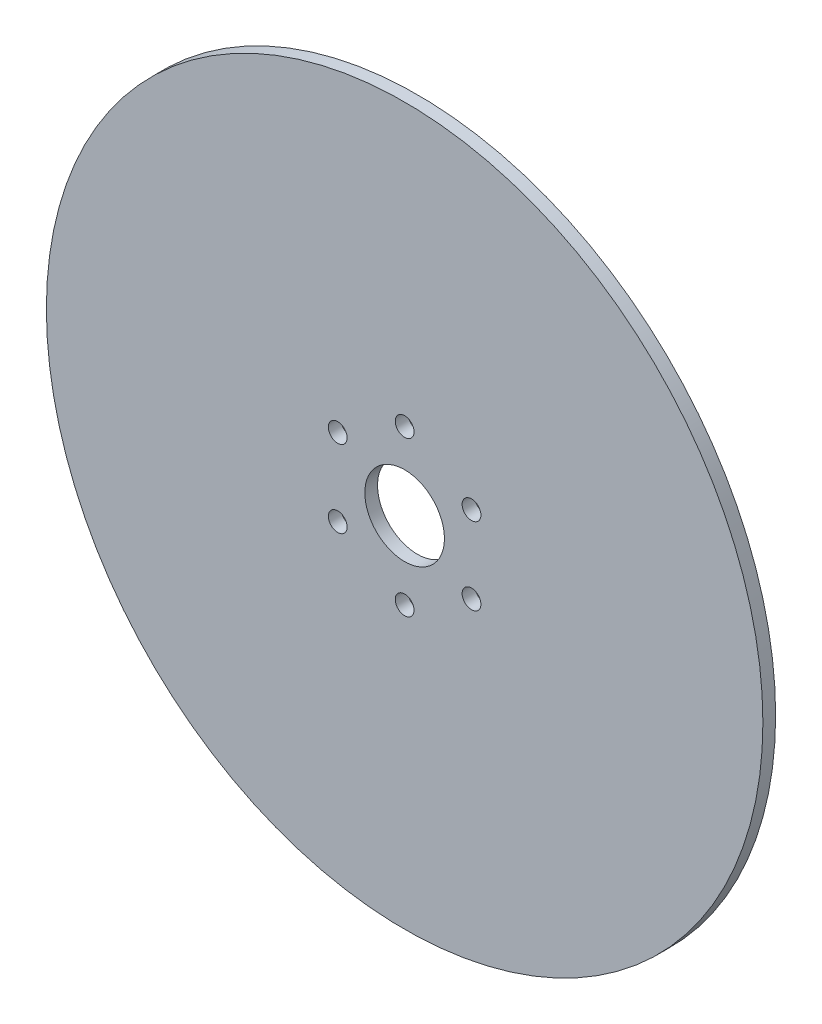
SolidWorks part; units mm, degrees
ref_plane "Front Plane" through (0, 0, 0) normal (0, 0, 1) x (1, 0, 0)
ref_plane "Top Plane" through (0, 0, 0) normal (0, 1, 0) x (1, 0, 0)
ref_plane "Right Plane" through (0, 0, 0) normal (1, 0, 0) x (0, 0, -1)
sketch "Sketch1" plane through (0, 0, 0) normal (0, 0, 1) x (1, 0, 0)
  circle A0 centre (0, 0) radius 114.3
  circle A1 centre (0, 0) radius 12.7
  dimension "D1" = 228.6
  dimension "D2" = 25.4
extrude "Boss-Extrude2" add sketch "Sketch1" along normal blind 4.064 contours A0
sketch "Sketch3" plane through (0, 0, 4.064) normal (0, 0, 1) x (1, 0, 0)
  circle A0 centre (0, 0) radius 12.7
  dimension "D1" = 25.4
extrude "Cut-Extrude1" cut sketch "Sketch3" along normal blind 70.612 and the other way blind 101.6
sketch "Sketch4" plane through (0, 0, 4.064) normal (0, 0, 1) x (1, 0, 0)
  line L0 (0, -12.7) -> (0, -24.638)
  circle A0 centre (0, 0) radius 12.7 construction
  circle A1 centre (0, -24.638) radius 2.9972
  circle A2 centre (-21.3371, -12.319) radius 2.9972
  circle A3 centre (-21.3371, 12.319) radius 2.9972
  circle A4 centre (0, 24.638) radius 2.9972
  circle A5 centre (21.3371, 12.319) radius 2.9972
  circle A6 centre (21.3371, -12.319) radius 2.9972
  point P20 (0, 0)
  dimension "D2" = 5.9944
  dimension "D1" = 11.938
  dimension "D3" = 6
extrude "Cut-Extrude3" cut sketch "Sketch4" against normal blind 70.612 contours A1 | A6 | A5 | A4 | A3 | A2
